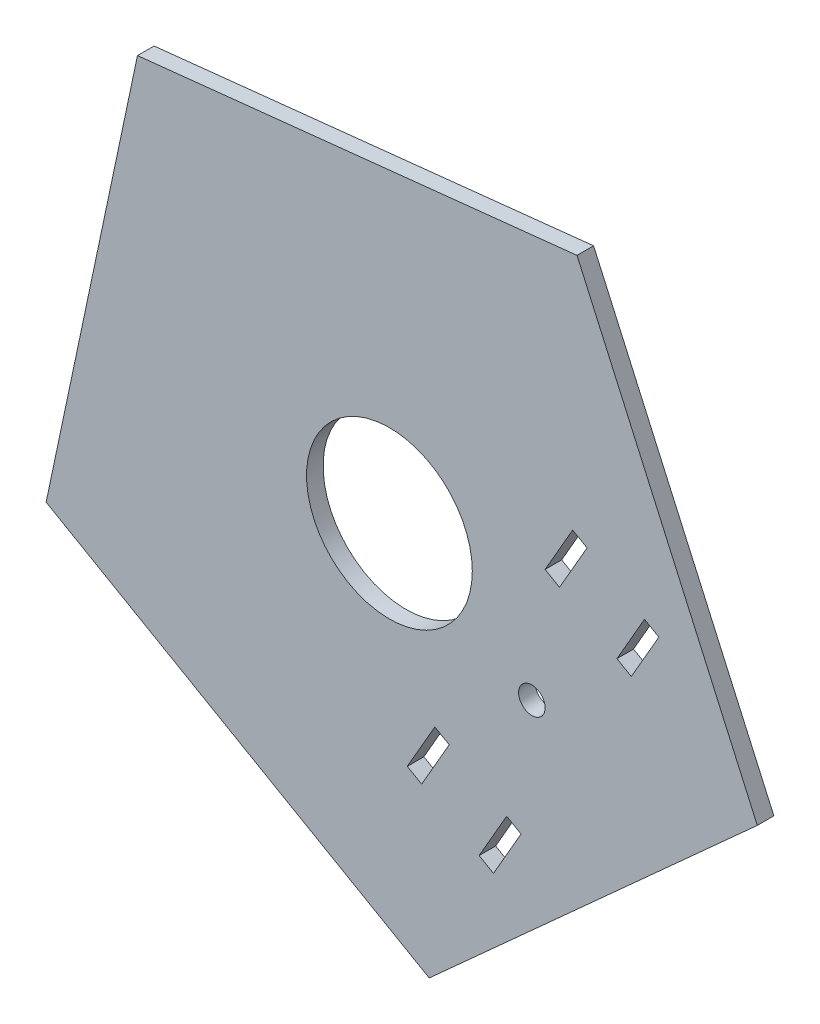
SolidWorks part; units mm, degrees
ref_plane "Front Plane" through (0, 0, 0) normal (0, 0, 1) x (1, 0, 0)
ref_plane "Top Plane" through (0, 0, 0) normal (0, 1, 0) x (1, 0, 0)
ref_plane "Right Plane" through (0, 0, 0) normal (1, 0, 0) x (0, 0, -1)
sketch "Sketch1" plane through (0, 0, 0) normal (0, 0, 1) x (1, 0, 0)
  line L1 (-62.1335, -27.7582) -> (7.1993, -67.6702)
  line L2 (7.1993, -67.6702) -> (66.5829, -14.0643)
  line L3 (66.5829, -14.0643) -> (33.9512, 58.978)
  line L4 (33.9512, 58.978) -> (-45.5999, 50.5147)
  line L5 (-45.5999, 50.5147) -> (-62.1335, -27.7582)
  circle A0 centre (0, 0) radius 55.0553 construction
  dimension "D1" = 80
extrude "Boss-Extrude1" add sketch "Sketch1" along normal blind 3 contours L4 L5 L1 L2 L3
sketch "Sketch3" plane through (0, 0, 3) normal (0, 0, 1) x (1, 0, 0)
  circle A0 centre (0, 0) radius 15
  point P29 (0, 0)
extrude "Cut-Extrude1" cut sketch "Sketch3" against normal blind 3 contours A0
sketch "Sketch5" plane through (0, 0, 3) normal (0, 0, 1) x (1, 0, 0)
  line L0 (0, 0) -> (25.9998, -14.967) construction
  line L1 (25.9998, -14.967) -> (32.4997, -18.7087) construction
  line L2 (32.4997, -18.7087) -> (20.0272, -40.3752) construction
  line L3 (21.3272, -41.1236) -> (18.7273, -39.6269)
  line L4 (21.2218, -35.2936) -> (23.8217, -36.7903)
  line L5 (21.2218, -35.2936) -> (16.2328, -43.9602)
  line L6 (23.8217, -36.7903) -> (18.8327, -45.4569)
  line L7 (16.2328, -43.9602) -> (18.8327, -45.4569)
  line L8 (21.2218, -35.2936) -> (18.8327, -45.4569) construction
  line L9 (23.8217, -36.7903) -> (16.2328, -43.9602) construction
  line L10 (25.9998, -14.967) -> (-24918.9853, -43347.9535) construction
  line L11 (8.2219, -27.8101) -> (3.2329, -36.4767)
  line L12 (5.8328, -37.9734) -> (3.2329, -36.4767)
  line L13 (10.8218, -29.3068) -> (5.8328, -37.9734)
  line L14 (10.8218, -29.3068) -> (8.2219, -27.8101)
  line L15 (30.7778, 5.3596) -> (28.1778, 6.8563)
  line L16 (30.7778, 5.3596) -> (35.7668, 14.0262)
  line L17 (35.7668, 14.0262) -> (33.1668, 15.5229)
  line L18 (28.1778, 6.8563) -> (33.1668, 15.5229)
  line L19 (43.7777, -2.1239) -> (48.7667, 6.5427)
  line L20 (46.1667, 8.0394) -> (48.7667, 6.5427)
  line L21 (41.1777, -0.6272) -> (46.1667, 8.0394)
  line L22 (41.1777, -0.6272) -> (43.7777, -2.1239)
  point P8 (20.0272, -40.3752)
  dimension "D2" = 7.5
  dimension "D4" = 3
  dimension "D1" = 30
  dimension "D3" = 25
  dimension "D5" = 10
  dimension "D6" = 3
extrude "Cut-Extrude3" cut sketch "Sketch5" against normal blind 3 contours L18 L15 L16 L17 | L21 L22 L19 L20 | L13 L12 L11 L14 | L6 L7 L5 L4
sketch "Sketch7" plane through (0, 0, 0) normal (0, 0, -1) x (-1, 0, 0)
  line L0 (0, 0) -> (-25.7831, -14.8423)
  circle A0 centre (-25.7831, -14.8423) radius 2.4
  dimension "D1" = 29.75
extrude "Cut-Extrude4" cut sketch "Sketch7" against normal blind 3
